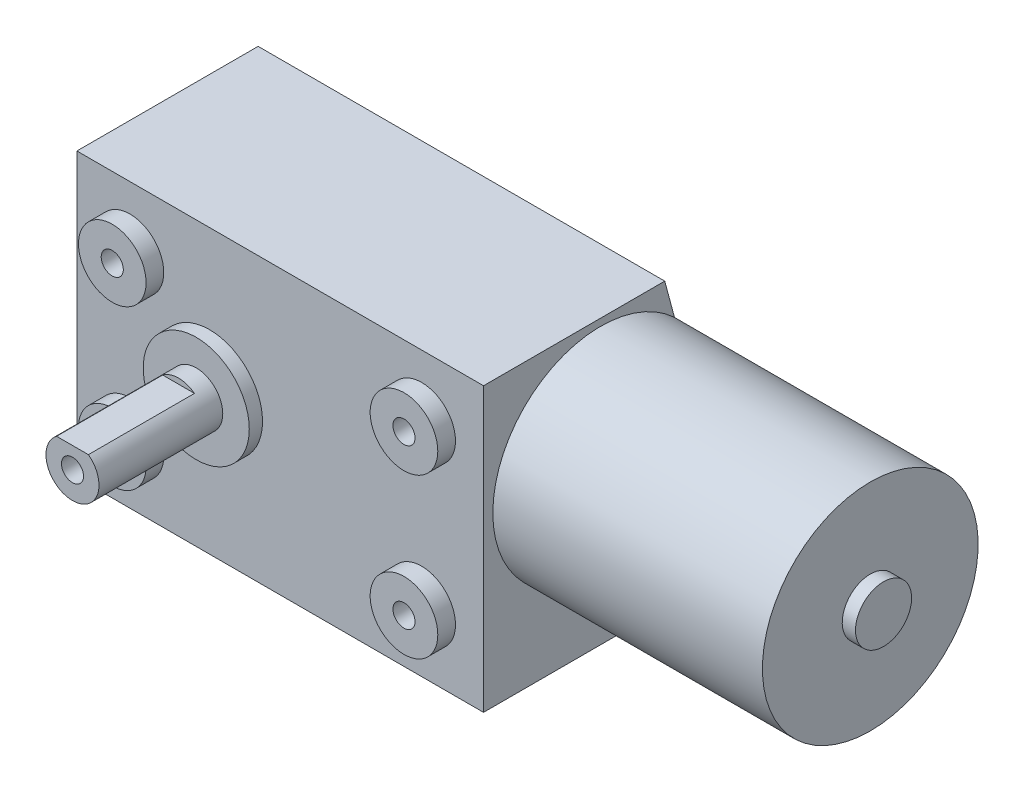
SolidWorks part; units mm, degrees
material "Plain Carbon Steel"
ref_plane "Front Plane" through (0, 0, 0) normal (0, 0, 1) x (1, 0, 0)
ref_plane "Top Plane" through (0, 0, 0) normal (0, 1, 0) x (1, 0, 0)
ref_plane "Right Plane" through (0, 0, 0) normal (1, 0, 0) x (0, 0, -1)
sketch "Sketch3" plane through (0, 0, 0) normal (0, 0, 1) x (1, 0, 0)
  line L0 (0, 0) -> (-15, 0) construction
  line L1 (-15, 16) -> (31, 16)
  line L2 (-15, 16) -> (-15, -16)
  line L3 (-15, -16) -> (31, -16)
  line L4 (31, 16) -> (31, -16)
  dimension "D1" = 15
  dimension "D2" = 32
  dimension "D3" = 46
extrude "Boss-Extrude1" add sketch "Sketch3" along normal mid plane 22.5
sketch "Sketch5" plane through (0, 0, 11.25) normal (0, 0, 1) x (1, 0, 0)
  line L0 (-9, -9) -> (-9, 9) construction
  line L1 (-9, 0) -> (0, 0) construction
  line L2 (24, -9) -> (-9, -9) construction
  line L3 (-9, 9) -> (24, 9) construction
  line L4 (24, 9) -> (24, -9) construction
  circle A0 centre (0, 0) radius 6
  circle A1 centre (-9, 9) radius 3.825
  circle A2 centre (-9, -9) radius 3.825
  circle A3 centre (24, 9) radius 3.825
  circle A4 centre (24, -9) radius 3.825
  dimension "D1" = 12
  dimension "D3" = 7.65
  dimension "D4" = 9
  dimension "D2" = 18
  dimension "D5" = 33
extrude "Boss-Extrude2" add sketch "Sketch5" along normal blind 1.5
other "Move Face1" face at (27.825, -9, 12.75) face at (27.825, 9, 12.75) face at (-5.175, -9, 12.75) face at (-5.175, 9, 12.75) parameters "D1"=0.5
sketch "Sketch6" plane through (0, 0, 12.75) normal (0, 0, 1) x (1, 0, 0)
  circle A0 centre (0, 0) radius 3
  dimension "D1" = 6
extrude "Boss-Extrude3" add sketch "Sketch6" along normal blind 14
sketch "Sketch7" plane through (0, 0, 26.75) normal (0, 0, 1) x (1, 0, 0)
  line L1 (-1.8, 3) -> (1.8, 3)
  line L2 (-1.8, 3) -> (-1.8, 2.4)
  line L3 (-1.8, 2.4) -> (1.8, 2.4)
  line L4 (1.8, 3) -> (1.8, 2.4)
  circle A0 centre (0, 0) radius 3 construction
  dimension "D1" = 2.4
extrude "Cut-Extrude1" cut sketch "Sketch7" against normal blind 12
hole_wizard "M3 Tapped Hole1" positions "Sketch10" profile "Sketch9" tap size "M3" standard "DIN"
sketch "Sketch10" plane through (0, 0, 13.25) normal (0, 0, 1) x (1, 0, 0)
  point P0 (-9, 9)
  point P3 (-9, -9)
  point P6 (24, 9)
  point P9 (24, -9)
sketch "Sketch9" plane through (-9, 9, 13.25) normal (1, 0, 0) x (0, -1, 0)
  line L0 (0, 0) -> (0, 9.2511)
  line L1 (0, 9.2511) -> (1.25, 8.5)
  line L2 (1.25, 8.5) -> (1.25, 0)
  line L5 (1.25, 0) -> (0, 0)
  line L10 (0, 9.2511) -> (-1.25, 8.5) construction
  line L11 (0, -6.35) -> (0, 107.95) construction
  dimension "Tap Drill Dia." = 2.5
  dimension "Tap Drill Depth" = 8.5
  dimension "Drill Angle" = 118
cosmetic thread "Hole Thread2" parameters "D1"=6, "D2"=3
cosmetic thread "Hole Thread3" parameters "D1"=6, "D2"=3
cosmetic thread "Hole Thread4" parameters "D1"=6, "D2"=3
cosmetic thread "Hole Thread5" parameters "D1"=6, "D2"=3
hole_wizard "M3 Tapped Hole2" positions "Sketch12" profile "Sketch11" tap size "M3" standard "DIN"
sketch "Sketch12" plane through (0, 0, 26.75) normal (0, 0, 1) x (1, 0, 0)
  point P0 (0, 0)
sketch "Sketch11" plane through (0, 0, 26.75) normal (1, 0, 0) x (0, -1, 0)
  line L0 (0, 0) -> (0, 9.2511)
  line L1 (0, 9.2511) -> (1.25, 8.5)
  line L2 (1.25, 8.5) -> (1.25, 0)
  line L5 (1.25, 0) -> (0, 0)
  line L10 (0, 9.2511) -> (-1.25, 8.5) construction
  line L11 (0, -6.35) -> (0, 107.95) construction
  dimension "Tap Drill Dia." = 2.5
  dimension "Tap Drill Depth" = 8.5
  dimension "Drill Angle" = 118
cosmetic thread "Hole Thread1" parameters "D1"=6, "D2"=3
chamfer "Chamfer1" distance 2 angle 75 2 edges at (8, -16, -11.25) (8, 16, -11.25)
sketch "Sketch13" plane through (31, 0, 0) normal (1, 0, 0) x (0, 0, -1)
  circle A0 centre (2, 3) radius 12.2
  dimension "D1" = 24.4
  dimension "D2" = 2
  dimension "D3" = 3
extrude "Boss-Extrude4" add sketch "Sketch13" along normal blind 30.5
sketch "Sketch14" plane through (61.5, 0, 0) normal (1, 0, 0) x (0, 0, -1)
  circle A0 centre (2, 3) radius 3.175
  dimension "D1" = 6.35
extrude "Boss-Extrude6" add sketch "Sketch14" along normal offset from surface (1.5 mm away) 78 up to face at (-15, 0, -3.0833)
